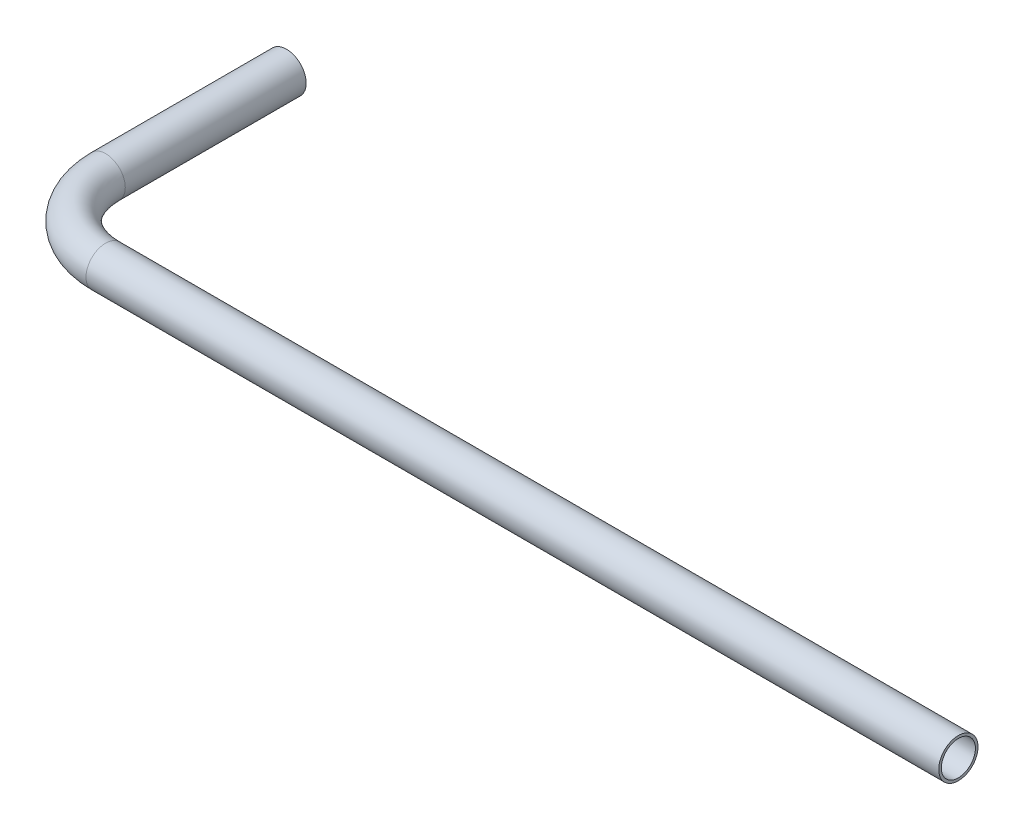
SolidWorks part; units mm, degrees
ref_plane "Front Plane" through (0, 0, 0) normal (0, 0, 1) x (1, 0, 0)
ref_plane "Top Plane" through (0, 0, 0) normal (0, 1, 0) x (1, 0, 0)
ref_plane "Right Plane" through (0, 0, 0) normal (1, 0, 0) x (0, 0, -1)
sketch "Sketch1" plane through (0, 0, 0) normal (0, 0, 1) x (1, 0, 0)
  circle A0 centre (0, 0) radius 4.191
  circle A1 centre (0, 0) radius 4.826
  dimension "D1" = 8.382
  dimension "D2" = 9.652
sketch3d "3DSketch1"
  line L0 (0, 0, 0) -> (0, 0, 44.45)
  line L1 (19.05, 0, 63.5) -> (228.6, 0, 63.5)
  arc A0 (0, 0, 44.45) -> (19.05, 0, 63.5) centre (19.05, 0, 44.45) ccw
  point P6 (0, 0, 63.5)
  point P7 (19.05, 19.05, 44.45)
  dimension "R1" = 19.05
  dimension "D2" = 63.5
  dimension "D3" = 228.6
sweep "Sweep1" add profiles "Sketch1" path "3DSketch1"
